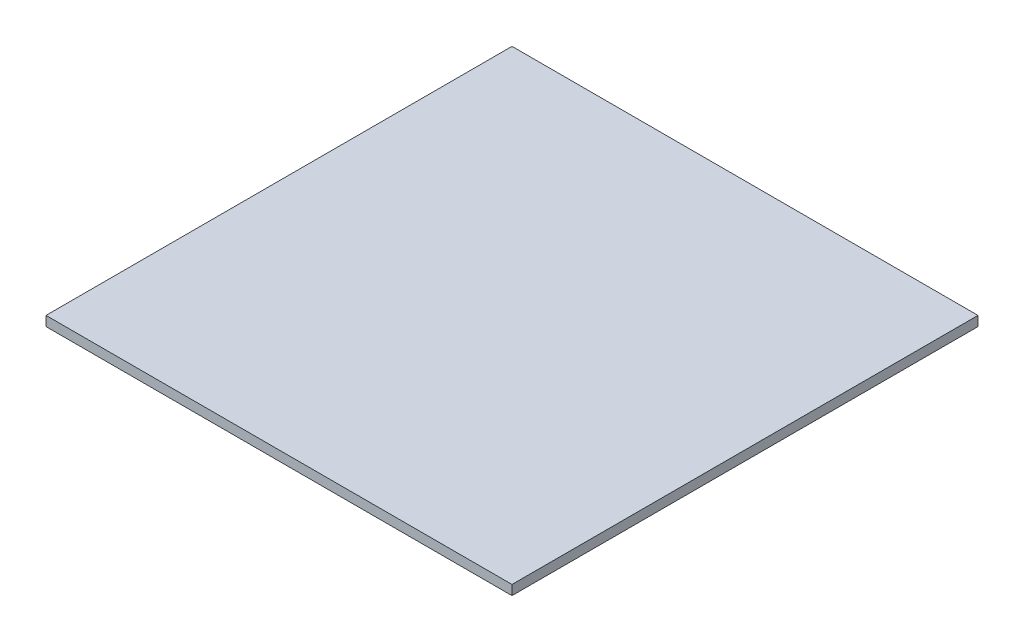
SolidWorks part; units mm, degrees
ref_plane "Front Plane" through (0, 0, 0) normal (0, 0, 1) x (1, 0, 0)
ref_plane "Top Plane" through (0, 0, 0) normal (0, 1, 0) x (1, 0, 0)
ref_plane "Right Plane" through (0, 0, 0) normal (1, 0, 0) x (0, 0, -1)
sketch "Sketch1" plane through (0, 0, 0) normal (0, 1, 0) x (1, 0, 0)
  line L1 (-152.4, 152.4) -> (152.4, 152.4)
  line L2 (-152.4, 152.4) -> (-152.4, -152.4)
  line L3 (-152.4, -152.4) -> (152.4, -152.4)
  line L4 (152.4, 152.4) -> (152.4, -152.4)
  line L5 (-152.4, 152.4) -> (152.4, -152.4) construction
  line L6 (-152.4, -152.4) -> (152.4, 152.4) construction
  point P0 (0, 0)
  dimension "D1" = 304.8
  dimension "12in" = 304.8
extrude "Boss-Extrude1" add sketch "Sketch1" along normal blind 6.35
